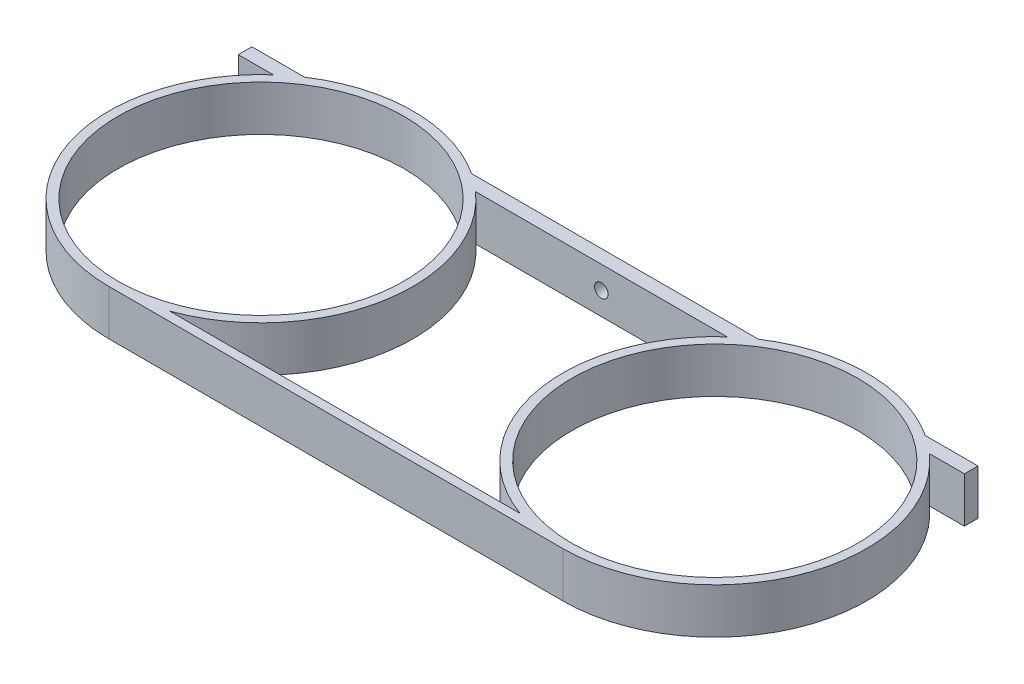
SolidWorks part; units mm, degrees
ref_plane "Front Plane" through (0, 0, 0) normal (0, 0, 1) x (1, 0, 0)
ref_plane "Top Plane" through (0, 0, 0) normal (0, 1, 0) x (1, 0, 0)
ref_plane "Right Plane" through (0, 0, 0) normal (1, 0, 0) x (0, 0, -1)
sketch "Sketch3" plane through (0, 0, 0) normal (0, 1, 0) x (1, 0, 0)
  line L0 (22.2991, 25) -> (77.7009, 25)
  line L1 (-30, 28) -> (-18.3916, 28)
  line L2 (-30, 28) -> (-30, 25)
  line L3 (-30, 25) -> (-22.2991, 25)
  line L4 (130, 28) -> (130, 25)
  line L5 (18.3916, 28) -> (81.6084, 28)
  line L6 (118.3916, 28) -> (130, 28)
  line L7 (122.2991, 25) -> (130, 25)
  line L8 (0, -33.5) -> (100, -33.5)
  line L10 (11.4018, -31.5) -> (88.5982, -31.5)
  circle A0 centre (0, 0) radius 31.5
  arc A1 (11.4018, -31.5) -> (22.2991, 25) centre (0, 0) ccw
  circle A2 centre (100, 0) radius 31.5
  arc A3 (100, -33.5) -> (122.2991, 25) centre (100, 0) ccw
  arc A4 (18.3916, 28) -> (-18.3916, 28) centre (0, 0) ccw
  circle A5 centre (0, 0) radius 33.5 construction
  arc A6 (77.7009, 25) -> (88.5982, -31.5) centre (100, 0) ccw
  arc A7 (118.3916, 28) -> (81.6084, 28) centre (100, 0) ccw
  arc A8 (-22.2991, 25) -> (0, -33.5) centre (0, 0) ccw
  point P25 (33.4707, 10.233)
  dimension "D2" = 63
  dimension "D4" = 30
  dimension "D5" = 30
  dimension "D6" = 25
  dimension "D7" = 3
  dimension "D1" = 2
  dimension "D3" = 2
extrude "Boss-Extrude5" add sketch "Sketch3" along normal blind 10
sketch "Sketch4" plane through (0, 0, -28) normal (0, 0, -1) x (-1, 0, 0)
  line L0 (-81.6084, 10) -> (-18.3916, 10) construction
  circle A0 centre (-50, 5) radius 1.5
  point P4 (-50, 10)
  dimension "D3" = 3
  dimension "D1" = 5
  dimension "D2" = 0
extrude "Cut-Extrude1" cut sketch "Sketch4" against normal blind 22
